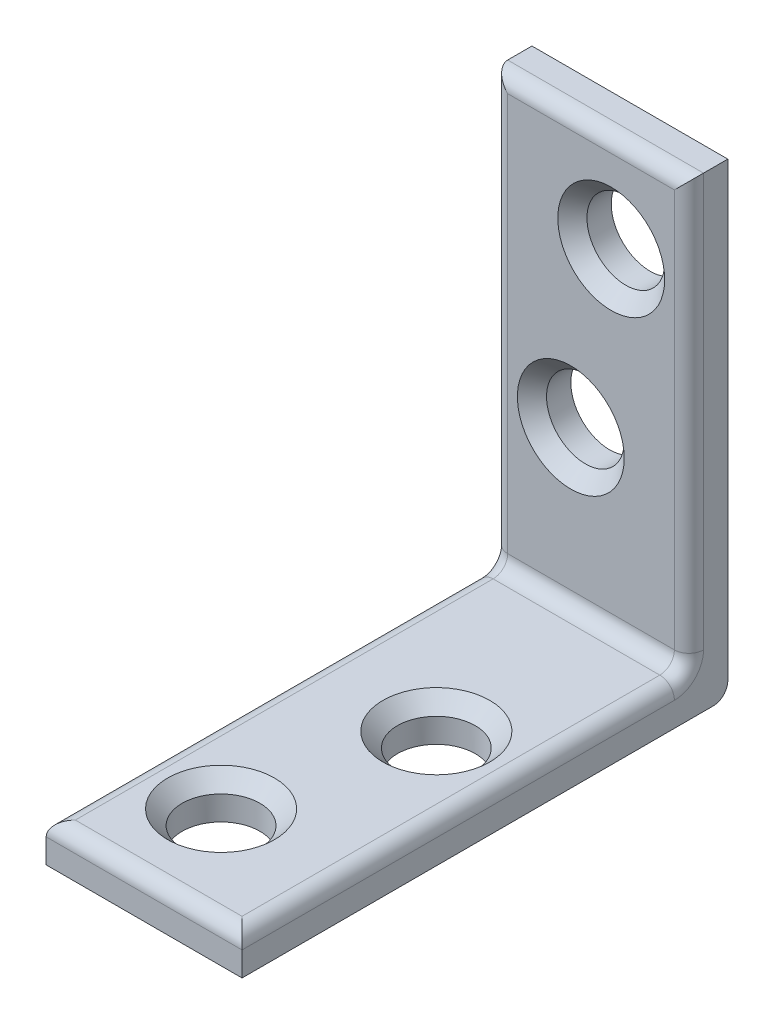
SolidWorks part; units mm, degrees
ref_plane "Front Plane" through (0, 0, 0) normal (0, 0, 1) x (1, 0, 0)
ref_plane "Top Plane" through (0, 0, 0) normal (0, 1, 0) x (1, 0, 0)
ref_plane "Right Plane" through (0, 0, 0) normal (1, 0, 0) x (0, 0, -1)
sketch "Sketch1" plane through (0, 0, 0) normal (0, 1, 0) x (1, 0, 0)
  line L1 (0, 0) -> (16.002, 0)
  line L2 (0, 0) -> (0, 38.1)
  line L3 (0, 38.1) -> (16.002, 38.1)
  line L4 (16.002, 0) -> (16.002, 38.1)
  dimension "D1" = 38.1
  dimension "D2" = 16.002
extrude "Boss-Extrude1" add sketch "Sketch1" along normal blind 3.175
sketch "Sketch2" plane through (0, 0, 0) normal (0, -1, 0) x (1, 0, 0)
  line L0 (16.002, 0) -> (16.002, -38.1) construction
  line L1 (0, -39.6875) -> (16.002, -39.6875)
  line L2 (0, -39.6875) -> (0, -36.5125)
  line L3 (0, -36.5125) -> (16.002, -36.5125)
  line L4 (16.002, -39.6875) -> (16.002, -36.5125)
  line L5 (16.002, -38.1) -> (0, -38.1) construction
  point P6 (0, -38.1)
  dimension "D1" = 16.002
  dimension "D2" = 3.175
extrude "Boss-Extrude2" add sketch "Sketch2" against normal blind 38.1
sketch "Sketch3" plane through (0, 0, -36.5125) normal (0, 0, 1) x (1, 0, 0)
  line L0 (16.002, 38.1) -> (0, 38.1) construction
  line L1 (0, 38.1) -> (0, 3.175) construction
  line L2 (16.002, 38.1) -> (16.002, 3.175) construction
  circle A0 centre (9.652, 30.1625) radius 3.175
  circle A1 centre (6.35, 15.875) radius 3.175
  dimension "D1" = 6.35
  dimension "D2" = 6.35
  dimension "D3" = 22.225
  dimension "D4" = 6.35
  dimension "D5" = 6.35
  dimension "D6" = 7.9375
extrude "Cut-Extrude1" cut sketch "Sketch3" against normal through all
sketch "Sketch4" plane through (0, 3.175, 0) normal (0, 1, 0) x (1, 0, 0)
  line L0 (16.002, 0) -> (16.002, 36.5125) construction
  line L2 (0, 0) -> (16.002, 0) construction
  line L3 (0, 36.5125) -> (0, 0) construction
  circle A0 centre (9.652, 22.225) radius 3.175
  circle A1 centre (6.35, 7.9375) radius 3.175
  point P8 (12.3421, 0)
  dimension "D1" = 6.35
  dimension "D2" = 6.35
  dimension "D3" = 6.35
  dimension "D4" = 22.225
  dimension "D5" = 7.9375
  dimension "D6" = 6.35
extrude "Cut-Extrude2" cut sketch "Sketch4" against normal through all
chamfer "Chamfer1" distance 1.1906 angle 45 4 edges at (9.525, 15.875, -36.5125) (12.827, 30.1625, -36.5125) (6.35, 3.175, -4.7625) (9.652, 3.175, -19.05)
fillet "Fillet1" radius 1.1906 8 edges at (8.001, 3.175, -36.5125) (8.001, 3.175, 0) (16.002, 3.175, -18.2562) (16.002, 20.6375, -36.5125) (8.001, 38.1, -36.5125) (0, 20.6375, -36.5125) (0, 3.175, -18.2562) (8.001, 0, -39.6875)
